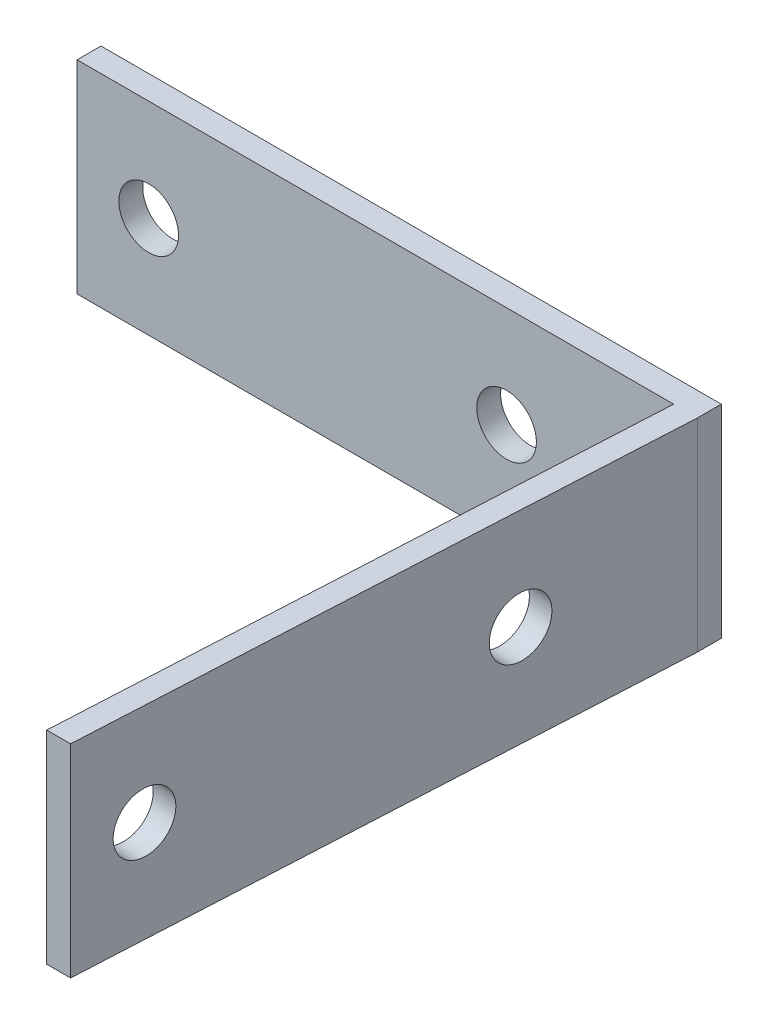
SolidWorks part; units mm, degrees
ref_plane "Plan de face" through (0, 0, 0) normal (0, 0, 1) x (1, 0, 0)
ref_plane "Plan de dessus" through (0, 0, 0) normal (0, 1, 0) x (1, 0, 0)
ref_plane "Plan de droite" through (0, 0, 0) normal (1, 0, 0) x (0, 0, -1)
sketch "Esquisse1" plane through (0, 0, 0) normal (0, 0, 1) x (1, 0, 0)
  line L1 (-26, 8.5) -> (26, 8.5)
  line L2 (-26, 8.5) -> (-26, -8.5)
  line L3 (-26, -8.5) -> (26, -8.5)
  line L4 (26, 8.5) -> (26, -8.5)
  line L5 (-26, 8.5) -> (26, -8.5) construction
  line L6 (-26, -8.5) -> (26, 8.5) construction
  point P0 (0, 0)
  dimension "D1" = 52
  dimension "D2" = 17
extrude "Boss.-Extru.1" add sketch "Esquisse1" along normal blind 2
sketch "Sketch1" plane through (0, -8.5, 0) normal (0, -1, 0) x (1, 0, 0)
  line L0 (26, 0) -> (25.3906, 11.6273) construction
  line L1 (26, 2) -> (26, 0) construction
  dimension "D1" = 3
sketch "Esquisse2" plane through (0, 0, 2) normal (0, 0, 1) x (1, 0, 0)
  line L0 (-26, -8.5) -> (26, -8.5) construction
  line L1 (26, 8.5) -> (24, 8.5)
  line L2 (26, 8.5) -> (26, -8.5)
  line L3 (26, -8.5) -> (24, -8.5)
  line L4 (24, 8.5) -> (24, -8.5)
  dimension "D1" = 2
extrude "Boss.-Extru.2" add sketch "Esquisse2" along direction (-0.0523, 0, 0.9986) on the side of the normal blind 50
sketch "Esquisse3" plane through (0, 0, 2) normal (0, 0, 1) x (1, 0, 0)
  line L0 (-26, 8.5) -> (-26, -8.5) construction
  line L1 (24, 8.5) -> (-26, 8.5) construction
  circle A0 centre (-20, 0) radius 2.5
  circle A1 centre (10, 0) radius 2.5
  point P6 (-26, 0)
  dimension "D2" = 5
  dimension "D3" = 8.5
  dimension "D5" = 5
  dimension "D1" = 6
  dimension "D4" = 30
  dimension "D6" = 8.5
extrude "Enlèv. mat.-Extru.1" cut sketch "Esquisse3" against normal blind 50
sketch "Esquisse4" plane through (24.0388, 0, 1.2598) normal (-0.9986, 0, -0.0523) x (-0.0523, 0, 0.9986)
  line L0 (50.7412, 8.5) -> (50.7412, -8.5) construction
  line L1 (50.7412, 8.5) -> (0.7412, 8.5) construction
  circle A0 centre (44.7412, 0) radius 2.5
  circle A1 centre (14.7412, 0) radius 2.5
  point P6 (50.7412, 0)
  dimension "D1" = 5
  dimension "D2" = 5
  dimension "D3" = 6
  dimension "D4" = 30
  dimension "D5" = 8.5
  dimension "D6" = 8.5
extrude "Enlèv. mat.-Extru.2" cut sketch "Esquisse4" against normal blind 50
